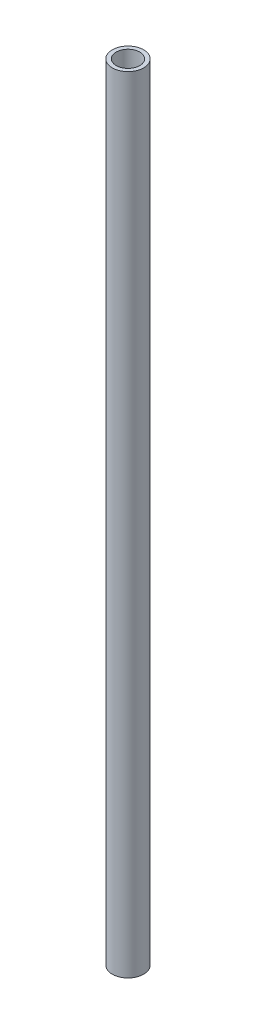
SolidWorks part; units mm, degrees
material "PEI"
ref_plane "Спереди" through (0, 0, 0) normal (0, 0, 1) x (1, 0, 0)
ref_plane "Сверху" through (0, 0, 0) normal (0, 1, 0) x (1, 0, 0)
ref_plane "Справа" through (0, 0, 0) normal (1, 0, 0) x (0, 0, -1)
sketch "Эскиз1" plane through (0, 0, 0) normal (0, 1, 0) x (1, 0, 0)
  circle A0 centre (0, 0) radius 20
  circle A1 centre (0, 0) radius 15
  dimension "D1" = 40
  dimension "D2" = 30
extrude "Бобышка-Вытянуть1" add sketch "Эскиз1" along normal blind 1000
